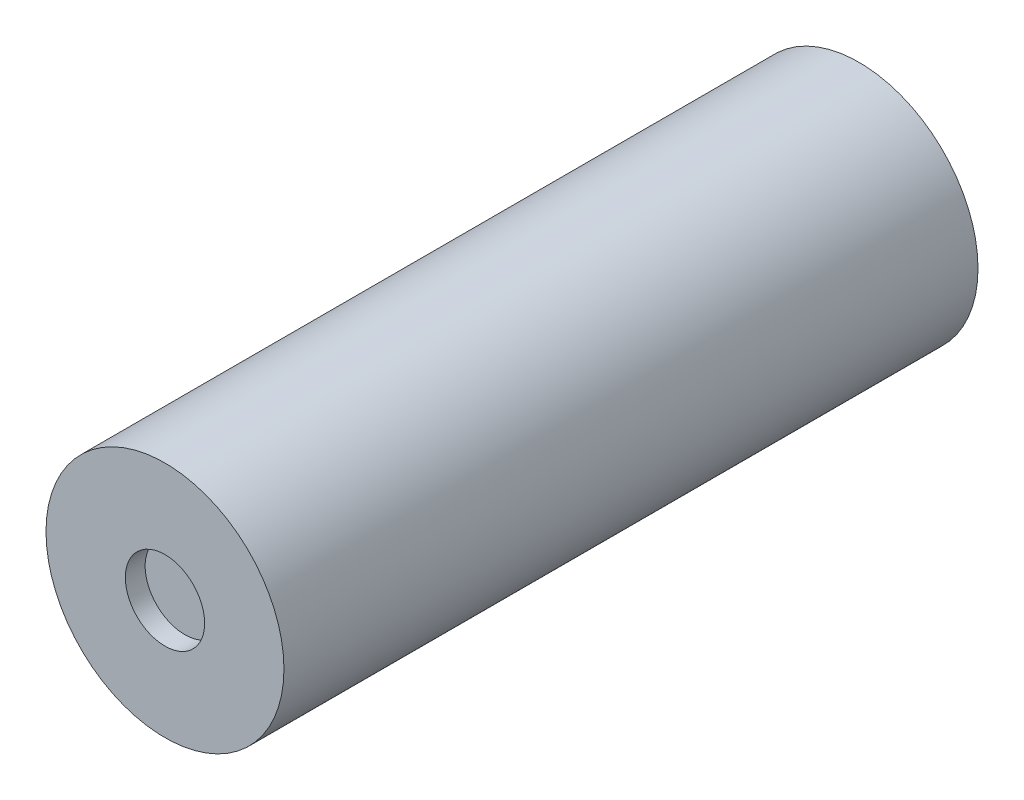
SolidWorks part; units mm, degrees
ref_plane "Ön Düzlem" through (0, 0, 0) normal (0, 0, 1) x (1, 0, 0)
ref_plane "Üst Düzlem" through (0, 0, 0) normal (0, 1, 0) x (1, 0, 0)
ref_plane "Sağ Düzlem" through (0, 0, 0) normal (1, 0, 0) x (0, 0, -1)
sketch "Çizim1" plane through (0, 0, 0) normal (0, 0, 1) x (1, 0, 0)
  circle A0 centre (0, 0) radius 30
  dimension "D1" = 60
extrude "Yükseklik-Ekstrüzyon1" add sketch "Çizim1" along normal blind 175
sketch "Çizim5" plane through (0, 0, 175) normal (0, 0, 1) x (1, 0, 0)
  circle A0 centre (0, 0) radius 10
  dimension "D1" = 20
extrude "Kes-Ekstrüzyon1" cut sketch "Çizim5" against normal blind 5
scale "Ölçek1" bodies to scale 105 scale about centroid uniform scaling yes scale factor 0.2
